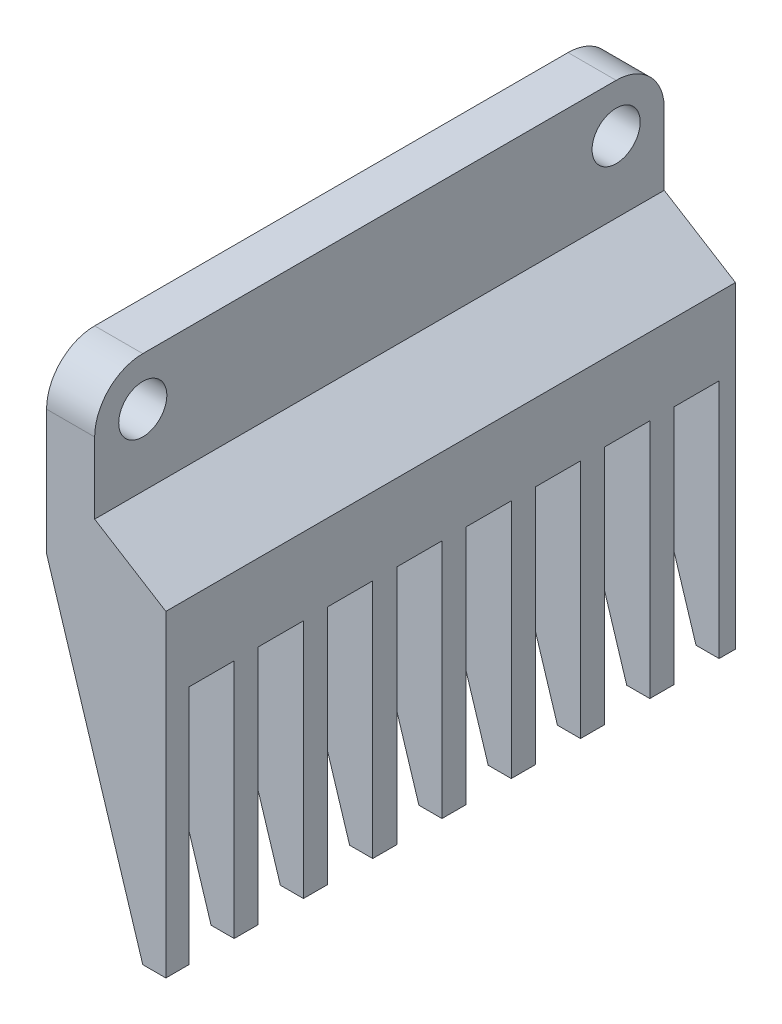
SolidWorks part; units mm, degrees
ref_plane "Front Plane" through (0, 0, 0) normal (0, 0, 1) x (1, 0, 0)
ref_plane "Top Plane" through (0, 0, 0) normal (0, 1, 0) x (1, 0, 0)
ref_plane "Right Plane" through (0, 0, 0) normal (1, 0, 0) x (0, 0, -1)
sketch "Sketch1" plane through (0, 0, 0) normal (0, 0, 1) x (1, 0, 0)
  line L0 (0, 0) -> (3.048, 0)
  line L1 (3.048, 0) -> (3.048, 41.91)
  line L2 (3.048, 41.91) -> (-6.35, 47.752)
  line L3 (-6.35, 47.752) -> (-6.35, 63.5)
  line L4 (-6.35, 63.5) -> (-12.7, 63.5)
  line L5 (-12.7, 63.5) -> (-12.7, 40.64)
  line L6 (-12.7, 40.64) -> (0, 0)
  dimension "D1" = 3.048
  dimension "D2" = 6.35
  dimension "D3" = 40.64
  dimension "D4" = 15.748
  dimension "D5" = 21.59
  dimension "D6" = 15.748
  dimension "D7" = 63.5
extrude "Boss-Extrude1" add sketch "Sketch1" along normal blind 75.184
fillet "Fillet1" radius 6.35 2 edges at (-9.525, 63.5, 0) (-9.525, 63.5, 75.184)
sketch "Sketch6" plane through (-6.35, 0, 0) normal (1, 0, 0) x (0, 0, -1)
  circle A0 centre (-68.834, 57.15) radius 3.175
  circle A1 centre (-6.35, 57.15) radius 3.175
  dimension "D1" = 6.35
  dimension "D2" = 6.35
extrude "Cut-Extrude2" cut sketch "Sketch6" against normal mid plane 125.984
sketch "Sketch11" plane through (3.048, 0, 0) normal (1, 0, 0) x (0, 0, -1)
  line L0 (-75.184, 0) -> (0, 0) construction
  line L1 (-72.136, 0) -> (-66.167, 0)
  line L2 (-72.136, 0) -> (-72.136, 31.75)
  line L3 (-72.136, 31.75) -> (-66.167, 31.75)
  line L4 (-66.167, 0) -> (-66.167, 31.75)
  line L5 (-75.184, 0) -> (-75.184, 41.91) construction
  line L6 (-62.992, 0) -> (-62.992, 31.75)
  line L7 (-62.992, 0) -> (-57.023, 0)
  line L8 (-57.023, 0) -> (-57.023, 31.75)
  line L9 (-62.992, 31.75) -> (-57.023, 31.75)
  line L10 (-53.848, 0) -> (-53.848, 31.75)
  line L11 (-53.848, 0) -> (-47.879, 0)
  line L12 (-47.879, 0) -> (-47.879, 31.75)
  line L13 (-53.848, 31.75) -> (-47.879, 31.75)
  line L14 (-44.704, 0) -> (-44.704, 31.75)
  line L15 (-44.704, 0) -> (-38.735, 0)
  line L16 (-38.735, 0) -> (-38.735, 31.75)
  line L17 (-44.704, 31.75) -> (-38.735, 31.75)
  line L18 (-35.56, 0) -> (-35.56, 31.75)
  line L19 (-35.56, 0) -> (-29.591, 0)
  line L20 (-29.591, 0) -> (-29.591, 31.75)
  line L21 (-35.56, 31.75) -> (-29.591, 31.75)
  line L22 (-26.416, 0) -> (-26.416, 31.75)
  line L23 (-26.416, 0) -> (-20.447, 0)
  line L24 (-20.447, 0) -> (-20.447, 31.75)
  line L25 (-26.416, 31.75) -> (-20.447, 31.75)
  line L26 (-17.272, 0) -> (-17.272, 31.75)
  line L27 (-17.272, 0) -> (-11.303, 0)
  line L28 (-11.303, 0) -> (-11.303, 31.75)
  line L29 (-17.272, 31.75) -> (-11.303, 31.75)
  line L30 (-8.128, 0) -> (-8.128, 31.75)
  line L31 (-8.128, 0) -> (-2.159, 0)
  line L32 (-2.159, 0) -> (-2.159, 31.75)
  line L33 (-8.128, 31.75) -> (-2.159, 31.75)
  line L38 (0, 0) -> (0, 41.91)
  line L39 (0, 41.91) -> (-75.184, 41.91)
  line L40 (-75.184, 41.91) -> (-75.184, 0)
  line L41 (-75.184, 0) -> (0, 0)
  line L42 (0, 0) -> (0, 41.91)
  line L43 (0, 41.91) -> (-75.184, 41.91)
  line L44 (-75.184, 41.91) -> (-75.184, 0)
  line L45 (-75.184, 0) -> (0, 0)
  line M13 (-75.184, 0) -> (0, 0)
  dimension "D1" = 31.75
  dimension "D2" = 3.048
  dimension "D3" = 5.969
  dimension "D5" = 9.144
  dimension "D6" = 0
  dimension "D4" = 8
extrude "Cut-Extrude6" cut sketch "Sketch11" against normal through all contours L4 L3 L2 M13 | L9 L6 L8 M13 | L13 L10 L12 M13 | L17 L14 L16 M13 | L21 L18 L20 M13 | L25 L22 L24 M13 | L29 L26 L28 M13 | L33 L30 L32 M13
